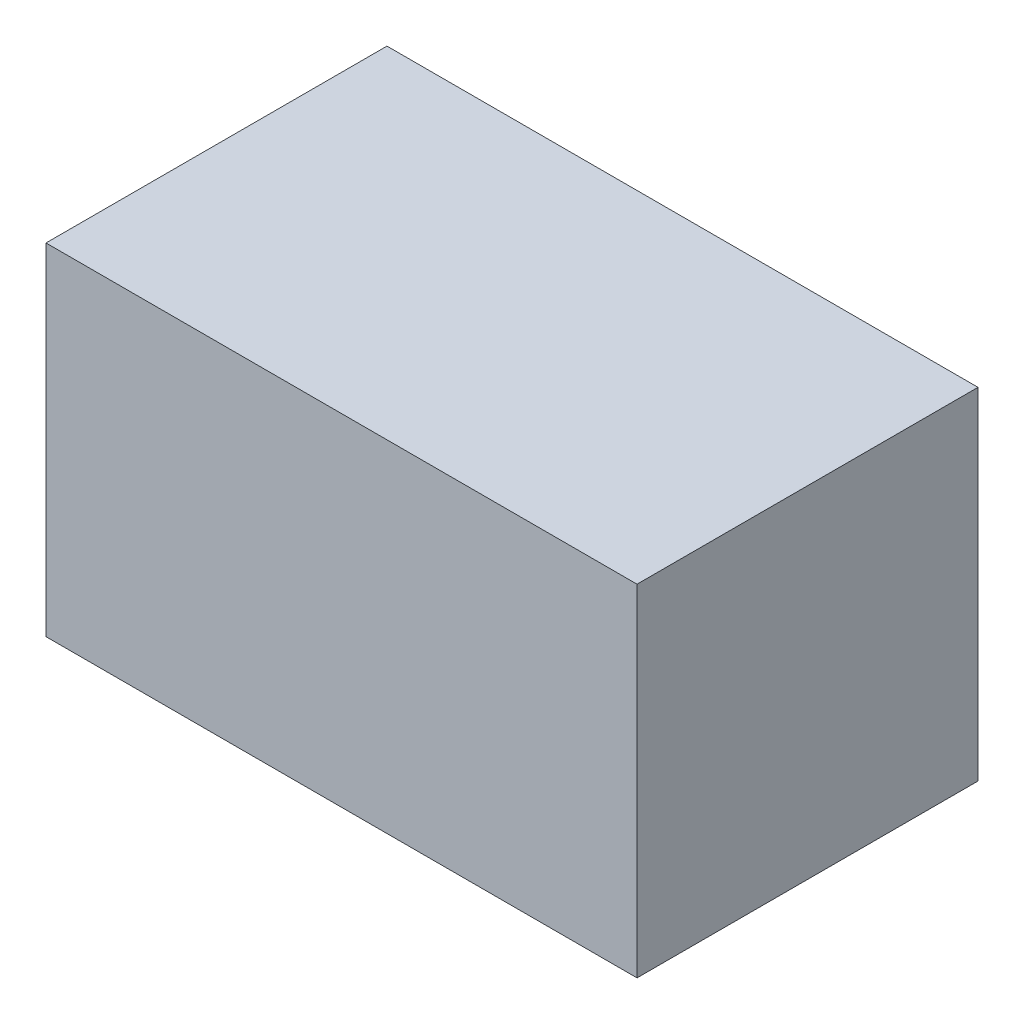
SolidWorks part; units mm, degrees
ref_plane "Front Plane" through (0, 0, 0) normal (0, 0, 1) x (1, 0, 0)
ref_plane "Top Plane" through (0, 0, 0) normal (0, 1, 0) x (1, 0, 0)
ref_plane "Right Plane" through (0, 0, 0) normal (1, 0, 0) x (0, 0, -1)
sketch "Sketch1" plane through (0, 0, 0) normal (0, 0, 1) x (1, 0, 0)
  line L1 (0, 0) -> (130, 0)
  line L2 (0, 0) -> (0, -75)
  line L3 (0, -75) -> (130, -75)
  line L4 (130, 0) -> (130, -75)
  dimension "D1" = 130
  dimension "D2" = 75
extrude "Boss-Extrude1" add sketch "Sketch1" along normal blind 75
